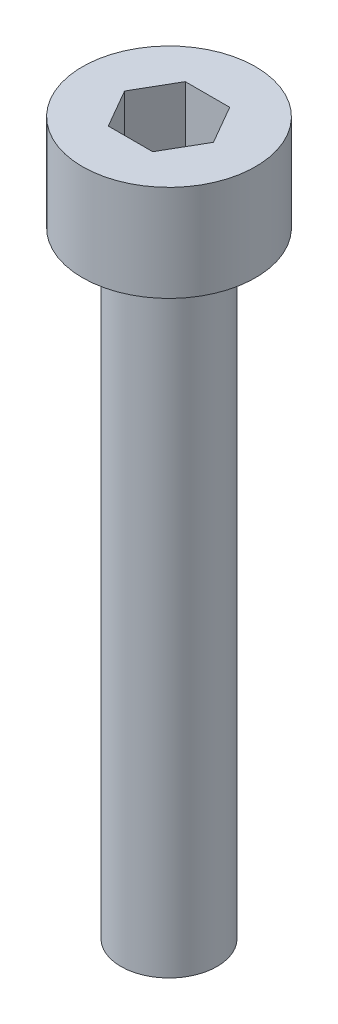
SolidWorks part; units mm, degrees
material "AISI 304"
ref_plane "Front Plane" through (0, 0, 0) normal (0, 0, 1) x (1, 0, 0)
ref_plane "Top Plane" through (0, 0, 0) normal (0, 1, 0) x (1, 0, 0)
ref_plane "Right Plane" through (0, 0, 0) normal (1, 0, 0) x (0, 0, -1)
sketch "Sketch1" plane through (0, 0, 0) normal (0, 0, 1) x (1, 0, 0)
  line L0 (0, 61.6916) -> (0, -59.3578) construction
  line L1 (0, -16) -> (1.25, -16)
  line L2 (1.25, -16) -> (1.25, 0)
  line L3 (1.25, 0) -> (2.25, 0)
  line L4 (2.25, 0) -> (2.25, 2.5)
  line L5 (2.25, 2.5) -> (0, 2.5)
  line L6 (0, 2.5) -> (0, -16)
  dimension "D1" = 16
  dimension "D2" = 4.5
  dimension "D3" = 2.5
  dimension "D4" = 2.5
revolve "Revolve1" add sketch "Sketch1" angle 360 about L0
sketch "Sketch2" plane through (0, 2.5, 0) normal (0, 1, 0) x (-1, 0, 0)
  line L1 (-0.5774, -1) -> (0.5774, -1)
  line L2 (0.5774, -1) -> (1.1547, 0)
  line L3 (1.1547, 0) -> (0.5774, 1)
  line L4 (0.5774, 1) -> (-0.5774, 1)
  line L5 (-0.5774, 1) -> (-1.1547, 0)
  line L6 (-1.1547, 0) -> (-0.5774, -1)
  circle A0 centre (0, 0) radius 1 construction
  dimension "D1" = 2
extrude "Cut-Extrude1" cut sketch "Sketch2" against normal blind 1.5
